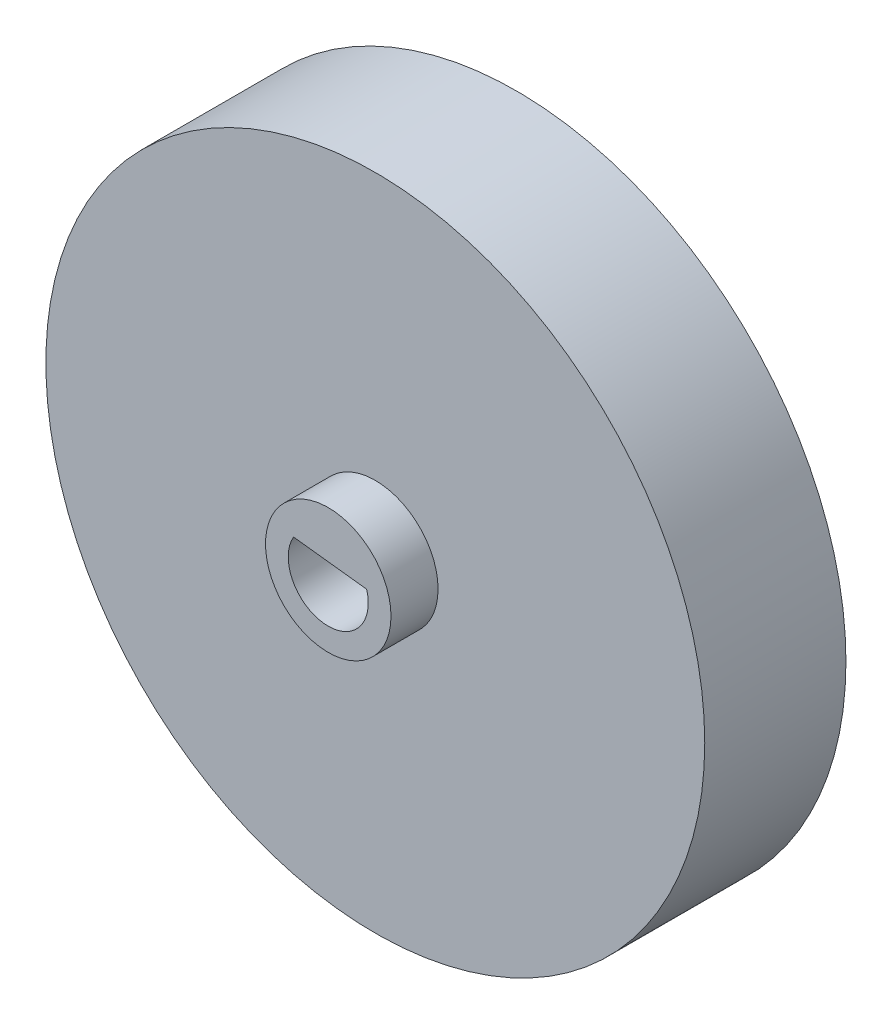
SolidWorks part; units mm, degrees
ref_plane "前视基准面" through (0, 0, 0) normal (0, 0, 1) x (1, 0, 0)
ref_plane "上视基准面" through (0, 0, 0) normal (0, 1, 0) x (1, 0, 0)
ref_plane "右视基准面" through (0, 0, 0) normal (1, 0, 0) x (0, 0, -1)
other "Configuration Table"
sketch "草图1" plane through (0, 0, 0) normal (0, 0, 1) x (1, 0, 0)
  line L0 (4.894, 1.4347) -> (-4.4239, 2.5376)
  circle A0 centre (0, 0) radius 8
  arc A1 (-4.4239, 2.5376) -> (4.894, 1.4347) centre (0, 0) ccw
extrude "凸台-拉伸1" add sketch "草图1" along normal blind 24
sketch "草图2" plane through (0, 0, 0) normal (0, 0, 1) x (1, 0, 0)
  circle A0 centre (0, 0) radius 42
  circle A1 centre (0, 0) radius 8
extrude "凸台-拉伸2" add sketch "草图2" along normal blind 18
sketch "草图3" plane through (0, 0, 0) normal (0, 0, 1) x (1, 0, 0)
  line L0 (37.5326, 2.0353) -> (37.5954, 2.0363)
  line L1 (37.5954, 2.0363) -> (37.7836, 2.0295)
  line L2 (37.7836, 2.0295) -> (38.0963, 2.0006)
  line L3 (38.0963, 2.0006) -> (38.531, 1.9351)
  line L4 (38.531, 1.9351) -> (39.0842, 1.9351)
  line L5 (39.0842, 1.9351) -> (39.751, 1.9351)
  line L6 (39.751, 1.9351) -> (40.5253, 1.3796)
  line L7 (40.5253, 1.3796) -> (41.4002, 1.3796)
  line L8 (41.9773, 1.3796) -> (42, 0)
  line L9 (42, 0) -> (41.9968, -0.5224)
  line L10 (41.9968, -0.5224) -> (41.987, -1.0447)
  line L11 (41.987, -1.0447) -> (40.5253, -1.0447)
  line L12 (40.5253, -1.0447) -> (39.751, -2.0353)
  line L13 (39.751, -2.0353) -> (39.0842, -2.0353)
  line L14 (39.0842, -2.0353) -> (38.531, -2.0353)
  line L15 (38.531, -2.0353) -> (38.0963, -2.0006)
  line L16 (38.0963, -2.0006) -> (37.5326, -2.0353)
  line L17 (37.5326, -2.0353) -> (37.5954, -2.0363)
  line L18 (37.5954, -2.0363) -> (37.5326, -2.0353)
  arc A0 (37.5326, -2.0353) -> (37.5326, 2.0353) centre (0, 0) ccw
  circle A1 centre (0, 0) radius 42 construction
